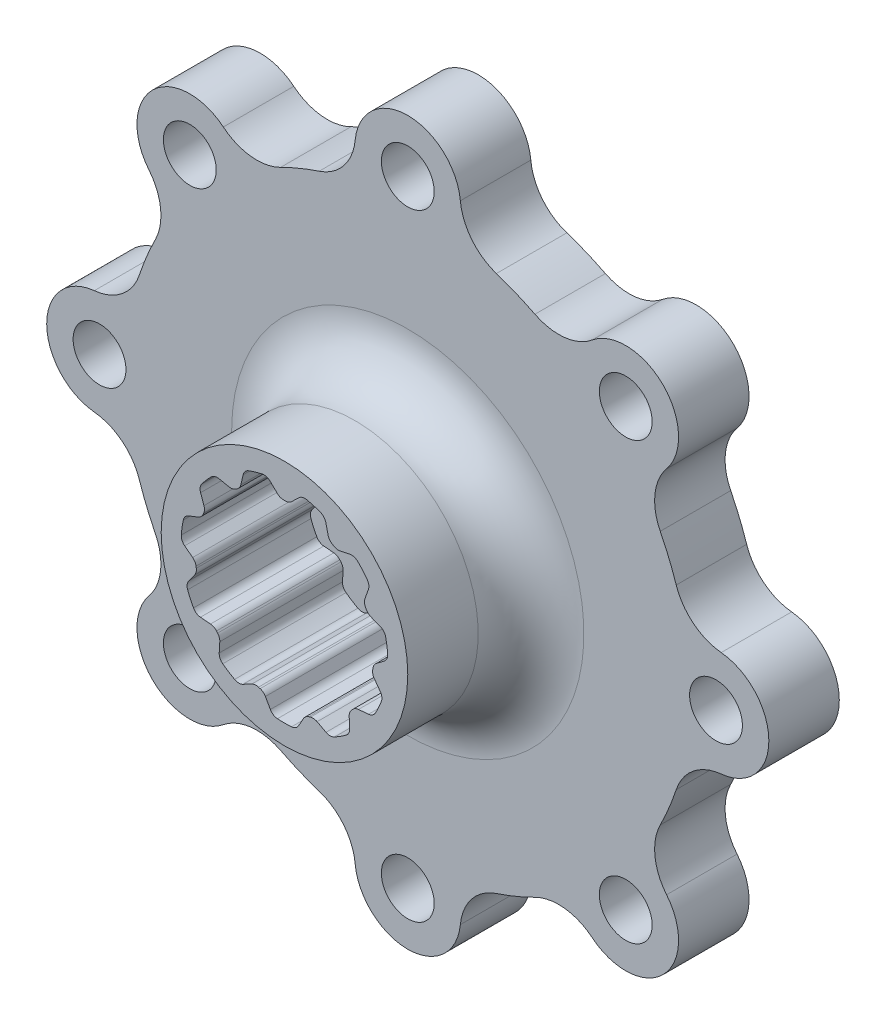
SolidWorks part; units mm, degrees
material "2024 Alloy"
ref_plane "Front Plane" through (0, 0, 0) normal (0, 0, 1) x (1, 0, 0)
ref_plane "Top Plane" through (0, 0, 0) normal (0, 1, 0) x (1, 0, 0)
ref_plane "Right Plane" through (0, 0, 0) normal (1, 0, 0) x (0, 0, -1)
sketch "Sketch2" plane through (0, 0, 0) normal (0, 0, 1) x (1, 0, 0)
  line L0 (-0.25, 5.0608) -> (0.25, 5.0608) construction
  line L1 (-0.25, 5.0608) -> (-1, 5.7893) construction
  line L2 (0.25, 5.0608) -> (1, 5.7893) construction
  line L3 (0, 5.0608) -> (0, 4.75) construction
  line L4 (0, 4.75) -> (-1.5096, 4.75) construction
  line L5 (0, 5.0608) -> (0, 5.875) construction
  line L6 (0, 5.875) -> (-1.4156, 5.875) construction
  line L7 (0, 0) -> (0, 4.75) construction
  arc A0 (-1, 5.7893) -> (1, 5.7893) centre (0, 0) cw construction
  circle A1 centre (0, 0) radius 7
  arc A2 (-0.25, 5.0608) -> (0.25, 5.0608) centre (0, 0) cw construction
  circle A3 centre (0, 0) radius 4.75 construction
  circle A4 centre (0, 0) radius 5.875
  dimension "D1" = 9.5
  dimension "D3" = 11.75
  dimension "D2" = 14
  dimension "D4" = 0.8142
  dimension "D5" = 2
  dimension "D6" = 0.5
extrude "Boss-Extrude1" add sketch "Sketch2" along normal blind 7
sketch "Sketch3" plane through (0, 0, 0) normal (0, 0, -1) x (-1, 0, 0)
  circle A0 centre (0, 0) radius 20.5
  dimension "D1" = 41
extrude "Boss-Extrude2" add sketch "Sketch3" along normal blind 1 contours A0
sketch "Sketch4" plane through (0, 0, -1) normal (0, 0, -1) x (-1, 0, 0)
  line L0 (0, 0) -> (0, 20.5) construction
  circle A0 centre (0, 0) radius 14.55
  circle A1 centre (0, 0) radius 20.5
  circle A2 centre (0, 0) radius 20.5 construction
  circle A3 centre (0, 0) radius 17.5 construction
  dimension "D1" = 29.1
  dimension "D2" = 35
extrude "Boss-Extrude3" add sketch "Sketch4" along normal blind 3
sketch "Sketch5" plane through (0, 0, -4) normal (0, 0, -1) x (-1, 0, 0)
  line L0 (0, 0) -> (0, 17.5) construction
  circle A0 centre (0, 0) radius 17.5 construction
  circle A1 centre (0, 17.5) radius 1.5
  dimension "D1" = 35
  dimension "D2" = 3
extrude "Cut-Extrude1" cut sketch "Sketch5" against normal up to surface (4 mm away) up to face at (5.875, 0, 0)
pattern_circular "CirPattern1" count 8 over 360 about axis through (0, 0, 0) along (0, 0, 1) of "Cut-Extrude1"
sketch "Sketch7" plane through (0, 0, 7) normal (0, 0, 1) x (1, 0, 0)
  line L0 (-0.25, 5.0608) -> (0.25, 5.0608) construction
  line L1 (-0.25, 5.0608) -> (-1, 5.7893)
  line L2 (0.25, 5.0608) -> (1, 5.7893)
  line L3 (0, 5.0608) -> (0, 4.75) construction
  line L4 (0, 4.75) -> (-1.5096, 4.75) construction
  line L5 (0, 5.0608) -> (0, 5.875) construction
  line L6 (0, 5.875) -> (-1.4156, 5.875) construction
  line L7 (0, 0) -> (0, 4.75) construction
  arc A0 (-1, 5.7893) -> (1, 5.7893) centre (0, 0) cw
  arc A1 (-0.25, 5.0608) -> (0.25, 5.0608) centre (0, 0) cw
  circle A2 centre (0, 0) radius 4.75 construction
  circle A3 centre (0, 0) radius 5.875 construction
  circle A4 centre (0, 0) radius 7 construction
  dimension "D1" = 9.5
  dimension "D2" = 11.75
  dimension "D3" = 0.8142
  dimension "D4" = 2
  dimension "D5" = 0.5
extrude "spline teeth" add sketch "Sketch7" against normal up to surface (7 mm away) up to face at (5.875, 0, 0)
fillet "Fillet1" radius 0.5 4 edges at (1, 5.7893, 3.5) (0.25, 5.0608, 3.5) (-0.25, 5.0608, 3.5) (-1, 5.7893, 3.5)
pattern_circular "CirPattern2" count 11 over 360 about axis through (0, 0, 0) along (0, 0, 1) of "Fillet1", "spline teeth"
sketch "Sketch8" plane through (0, 0, -1) normal (0, 0, -1) x (-1, 0, 0)
  circle A0 centre (0, 0) radius 5.45
  circle A1 centre (0, 0) radius 4.45
  dimension "D1" = 10.9
  dimension "D2" = 1
extrude "Boss-Extrude4" add sketch "Sketch8" along normal up to surface (3 mm away) up to face at (11.3137, 13.435, -4)
sketch "Sketch9" plane through (0, 0, -4) normal (0, 0, -1) x (-1, 0, 0)
  line L0 (-14.4957, 10.253) -> (-13.2704, 9.0277)
  line L1 (-10.253, 14.4957) -> (-9.0277, 13.2704)
  line L2 (-14.4957, 14.4957) -> (-12.3744, 12.3744) construction
  line L3 (-3, 17.5) -> (-3, 15.7671)
  line L4 (3, 17.5) -> (3, 15.7671)
  line L5 (0, 20.5) -> (0, 17.5) construction
  line L6 (10.253, 14.4957) -> (9.0277, 13.2704)
  line L7 (14.4957, 10.253) -> (13.2704, 9.0277)
  line L8 (14.4957, 14.4957) -> (12.3744, 12.3744) construction
  line L9 (17.5, 3) -> (15.7671, 3)
  line L10 (17.5, -3) -> (15.7671, -3)
  line L11 (20.5, 0) -> (17.5, 0) construction
  line L12 (14.4957, -10.253) -> (13.2704, -9.0277)
  line L13 (10.253, -14.4957) -> (9.0277, -13.2704)
  line L14 (14.4957, -14.4957) -> (12.3744, -12.3744) construction
  line L15 (3, -17.5) -> (3, -15.7671)
  line L16 (-3, -17.5) -> (-3, -15.7671)
  line L17 (0, -20.5) -> (0, -17.5) construction
  line L18 (-10.253, -14.4957) -> (-9.0277, -13.2704)
  line L19 (-14.4957, -10.253) -> (-13.2704, -9.0277)
  line L20 (-14.4957, -14.4957) -> (-12.3744, -12.3744) construction
  line L21 (-17.5, -3) -> (-15.7671, -3)
  line L22 (-17.5, 3) -> (-15.7671, 3)
  line L23 (-20.5, 0) -> (-17.5, 0) construction
  arc A0 (-10.253, 14.4957) -> (-14.4957, 10.253) centre (-12.3744, 12.3744) ccw
  circle A1 centre (0, 0) radius 20.5 construction
  arc A2 (3, 17.5) -> (-3, 17.5) centre (0, 17.5) ccw
  arc A3 (14.4957, 10.253) -> (10.253, 14.4957) centre (12.3744, 12.3744) ccw
  arc A4 (17.5, -3) -> (17.5, 3) centre (17.5, 0) ccw
  arc A5 (10.253, -14.4957) -> (14.4957, -10.253) centre (12.3744, -12.3744) ccw
  arc A6 (-3, -17.5) -> (3, -17.5) centre (0, -17.5) ccw
  arc A7 (-14.4957, -10.253) -> (-10.253, -14.4957) centre (-12.3744, -12.3744) ccw
  arc A8 (-17.5, 3) -> (-17.5, -3) centre (-17.5, 0) ccw
  arc A9 (-13.2704, 9.0277) -> (-15.7671, 3) centre (0, 0) ccw
  circle A10 centre (0, 0) radius 14.55 construction
  circle A11 centre (0, 0) radius 21.5
  arc A12 (-3, 15.7671) -> (-9.0277, 13.2704) centre (0, 0) ccw
  arc A13 (9.0277, 13.2704) -> (3, 15.7671) centre (0, 0) ccw
  arc A14 (15.7671, 3) -> (13.2704, 9.0277) centre (0, 0) ccw
  arc A15 (13.2704, -9.0277) -> (15.7671, -3) centre (0, 0) ccw
  arc A16 (3, -15.7671) -> (9.0277, -13.2704) centre (0, 0) ccw
  arc A17 (-9.0277, -13.2704) -> (-3, -15.7671) centre (0, 0) ccw
  arc A18 (-15.7671, -3) -> (-13.2704, -9.0277) centre (0, 0) ccw
  point P58 (0, 0)
  dimension "D2" = 1.5
  dimension "D3" = 1
  dimension "D1" = 8
extrude "Cut-Extrude3" cut sketch "Sketch9" against normal up to surface (4 mm away) up to face at (10.8744, 12.3744, 0)
fillet "Fillet2" radius 3 16 edges at (-15.7671, -3, -2) (-15.7671, 3, -2) (-13.2704, 9.0277, -2) (-9.0277, 13.2704, -2) (-3, 15.7671, -2) (3, 15.7671, -2) (9.0277, 13.2704, -2) (15.7671, 3, -2) (3, -15.7671, -2) (13.2704, -9.0277, -2) (13.2704, 9.0277, -2) (15.7671, -3, -2) (9.0277, -13.2704, -2) (-3, -15.7671, -2) (-9.0277, -13.2704, -2) (-13.2704, -9.0277, -2)
fillet "Fillet3" radius 3 1 edges at (-7, 0, 0)
